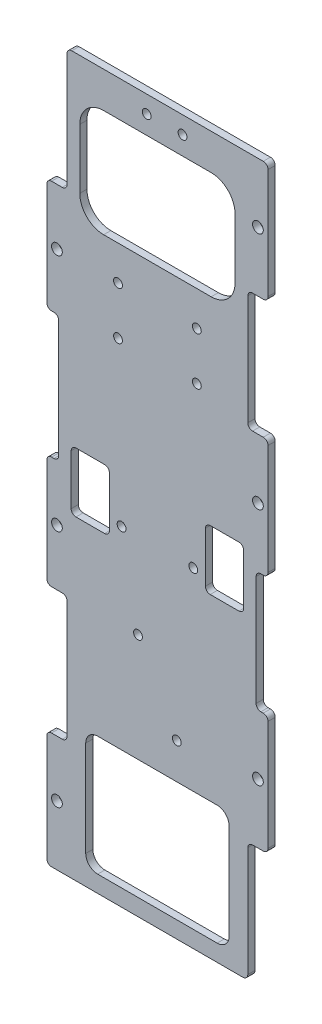
SolidWorks part; units mm, degrees
material "Acrylic (Medium-high impact)"
ref_plane "Front Plane" through (0, 0, 0) normal (0, 0, 1) x (1, 0, 0)
ref_plane "Top Plane" through (0, 0, 0) normal (0, 1, 0) x (1, 0, 0)
ref_plane "Right Plane" through (0, 0, 0) normal (1, 0, 0) x (0, 0, -1)
sketch "Sketch1" plane through (0, 0, 0) normal (0, 0, 1) x (1, 0, 0)
  line L1 (46.3, -150) -> (-46.3, -150)
  line L2 (46.3, -150) -> (46.3, 150)
  line L3 (46.3, 150) -> (-46.3, 150)
  line L4 (-46.3, -150) -> (-46.3, 150)
  line L5 (46.3, -150) -> (-46.3, 150) construction
  line L6 (46.3, 150) -> (-46.3, -150) construction
  point P0 (0, 0)
  dimension "D1" = 300
  dimension "D2" = 92.6
extrude "Boss-Extrude1" add sketch "Sketch1" along normal blind 3
sketch "Sketch3" plane through (0, 0, 0) normal (0, 0, 1) x (1, 0, 0)
  line L0 (-42.06, 151.5) -> (-42.06, -150) construction
  line L1 (42.06, 150) -> (42.06, -148.5) construction
  line L2 (-37.82, 98.5) -> (-46.3, 98.5)
  line L3 (-37.82, 98.5) -> (-37.82, 150)
  line L4 (-37.82, 150) -> (-46.3, 150)
  line L5 (-46.3, 98.5) -> (-46.3, 150)
  line L6 (-37.82, 98.5) -> (-46.3, 150) construction
  line L7 (-37.82, 150) -> (-46.3, 98.5) construction
  line L8 (37.82, 100) -> (46.3, 100)
  line L9 (37.82, 100) -> (37.82, 50)
  line L10 (37.82, 50) -> (46.3, 50)
  line L11 (46.3, 100) -> (46.3, 50)
  line L12 (37.82, 100) -> (46.3, 50) construction
  line L13 (37.82, 50) -> (46.3, 100) construction
  line L14 (46.3, -50) -> (41.3, -50)
  line L15 (46.3, -50) -> (46.3, 0)
  line L16 (46.3, 0) -> (41.3, 0)
  line L17 (41.3, -50) -> (41.3, 0)
  line L18 (46.3, -50) -> (41.3, 0) construction
  line L19 (46.3, 0) -> (41.3, -50) construction
  line L20 (-41.3, -1.5) -> (-46.3, -1.5)
  line L21 (-41.3, -1.5) -> (-41.3, 51.5)
  line L22 (-41.3, 51.5) -> (-46.3, 51.5)
  line L23 (-46.3, -1.5) -> (-46.3, 51.5)
  line L24 (-41.3, -1.5) -> (-46.3, 51.5) construction
  line L25 (-41.3, 51.5) -> (-46.3, -1.5) construction
  line L26 (-37.82, -101.5) -> (-46.3, -101.5)
  line L27 (-37.82, -101.5) -> (-37.82, -48.5)
  line L28 (-37.82, -48.5) -> (-46.3, -48.5)
  line L29 (-46.3, -101.5) -> (-46.3, -48.5)
  line L30 (-37.82, -101.5) -> (-46.3, -48.5) construction
  line L31 (-37.82, -48.5) -> (-46.3, -101.5) construction
  line L32 (37.82, -150) -> (46.3, -150)
  line L33 (37.82, -150) -> (37.82, -100)
  line L34 (37.82, -100) -> (46.3, -100)
  line L35 (46.3, -150) -> (46.3, -100)
  line L36 (37.82, -150) -> (46.3, -100) construction
  line L37 (37.82, -100) -> (46.3, -150) construction
  line L38 (42.06, 50) -> (-134.3061, 50) construction
  line L39 (46.3, 150) -> (-46.3, 150) construction
  line L40 (-46.3, -150) -> (46.3, -150) construction
  line L41 (46.3, -150) -> (46.3, 150) construction
  line L42 (-46.3, 150) -> (-46.3, -150) construction
  circle A0 centre (-42.06, 75) radius 2.25
  circle A1 centre (42.06, 125) radius 2.25
  circle A2 centre (42.06, 25) radius 2.25
  circle A3 centre (42.06, -75) radius 2.25
  circle A4 centre (-42.06, -25) radius 2.25
  circle A5 centre (-42.06, -125) radius 2.25
  point P8 (-42.06, 124.25)
  point P10 (-42.06, 25)
  point P19 (42.06, 75)
  point P24 (-42.06, -75)
  point P32 (43.8, -25)
  point P39 (42.06, -125)
  dimension "D1" = 4.5
  dimension "D2" = 4.5
  dimension "D12" = 4.5
  dimension "D14" = 4.5
  dimension "D20" = 4.5
  dimension "D22" = 4.5
  dimension "D3" = 25
  dimension "D4" = 84.12
  dimension "D5" = 8.48
  dimension "D6" = 51.5
  dimension "D7" = 8.48
  dimension "D8" = 50
  dimension "D9" = 50
  dimension "D10" = 5
  dimension "D11" = 75
  dimension "D13" = 125
  dimension "D15" = 100
  dimension "D16" = 53
  dimension "D17" = 53
  dimension "D18" = 8.48
  dimension "D19" = 75
  dimension "D21" = 50
  dimension "D23" = 5
  dimension "D24" = 100
  dimension "D25" = 42.06
  dimension "D26" = 0
  dimension "D27" = 0
  dimension "D28" = 0
  dimension "D29" = 0
  dimension "D30" = 175
  dimension "D31" = 25
  dimension "D32" = 125
  dimension "D33" = 75
  dimension "D34" = 0
  dimension "D35" = 0
extrude "Cut-Extrude2" cut sketch "Sketch3" along normal blind 10
fillet "Fillet1" radius 2 24 edges at (-41.3, -1.5, 1.5) (-46.3, -1.5, 1.5) (-46.3, -48.5, 1.5) (-37.82, -48.5, 1.5) (-37.82, -101.5, 1.5) (-46.3, -101.5, 1.5) (-46.3, -150, 1.5) (37.82, -150, 1.5) (37.82, -100, 1.5) (46.3, -100, 1.5) (46.3, -50, 1.5) (41.3, -50, 1.5) (41.3, 0, 1.5) (46.3, 0, 1.5) (46.3, 50, 1.5) (37.82, 50, 1.5) (37.82, 100, 1.5) (46.3, 100, 1.5) (46.3, 150, 1.5) (-37.82, 150, 1.5) (-37.82, 98.5, 1.5) (-46.3, 98.5, 1.5) (-41.3, 51.5, 1.5) (-46.3, 51.5, 1.5)
sketch "Sketch4" plane through (0, 0, 0) normal (0, 0, -1) x (-1, 0, 0)
  circle A2 centre (8.125, -47.8) radius 1.85
  circle A3 centre (-8.125, -78) radius 1.85
  dimension "D1" = 3.7
  dimension "D2" = 3.7
extrude "Cut-Extrude3" cut sketch "Sketch4" against normal blind 5
sketch "Sketch5" plane through (0, 0, 0) normal (0, 0, -1) x (-1, 0, 0)
  line L10 (-34.8, -5.6) -> (34.8, -5.6) construction
  line L15 (-34.8, 3.65) -> (-34.8, -14.85) construction
  line L17 (34.8, -14.85) -> (34.8, 3.65) construction
  line L18 (-28.1, 3.65) -> (-28.1, -17) construction
  line L19 (-21.4, 3.65) -> (-34.8, 3.65) construction
  line L20 (-33.6, -17) -> (-22.6, -17) construction
  line L21 (28.1, 3.65) -> (28.1, -17) construction
  line L22 (34.8, 3.65) -> (21.4, 3.65) construction
  line L23 (22.6, -17) -> (33.6, -17) construction
  line L25 (-22.1, -18.1) -> (-34.1, -18.1)
  line L26 (-20.1, -16.1) -> (-20.1, 4.9)
  line L27 (-22.1, 6.9) -> (-34.1, 6.9)
  line L28 (-36.1, -16.1) -> (-36.1, 4.9)
  line L29 (-20.1, -18.1) -> (-36.1, 6.9) construction
  line L30 (-20.1, 6.9) -> (-36.1, -18.1) construction
  line L31 (34.1, -18.1) -> (22.1, -18.1)
  line L32 (36.1, -16.1) -> (36.1, 4.9)
  line L33 (34.1, 6.9) -> (22.1, 6.9)
  line L34 (20.1, -16.1) -> (20.1, 4.9)
  line L35 (36.1, -18.1) -> (20.1, 6.9) construction
  line L36 (36.1, 6.9) -> (20.1, -18.1) construction
  circle A15 centre (-15, -12) radius 1.85
  circle A16 centre (15, -12) radius 1.85
  arc A17 (22.1, -18.1) -> (20.1, -16.1) centre (22.1, -16.1) cw
  arc A18 (34.1, -18.1) -> (36.1, -16.1) centre (34.1, -16.1) ccw
  arc A19 (36.1, 4.9) -> (34.1, 6.9) centre (34.1, 4.9) ccw
  arc A20 (22.1, 6.9) -> (20.1, 4.9) centre (22.1, 4.9) ccw
  arc A21 (-34.1, -18.1) -> (-36.1, -16.1) centre (-34.1, -16.1) cw
  arc A22 (-20.1, 4.9) -> (-22.1, 6.9) centre (-22.1, 4.9) ccw
  arc A23 (-22.1, -18.1) -> (-20.1, -16.1) centre (-22.1, -16.1) ccw
  arc A24 (-34.1, 6.9) -> (-36.1, 4.9) centre (-34.1, 4.9) ccw
  point P20 (-28.1, -5.6)
  point P25 (28.1, -5.6)
  dimension "D1" = 16
  dimension "D2" = 25
  dimension "D3" = 25
  dimension "D5" = 3.7
  dimension "D6" = 3.7
  dimension "D7" = 2
  dimension "D4" = 16
extrude "Cut-Extrude4" cut sketch "Sketch5" against normal blind 10
sketch "Sketch6" plane through (0, 0, 0) normal (0, 0, -1) x (-1, 0, 0)
  circle A4 centre (16.5, 55.5) radius 1.85
  circle A5 centre (-16.5, 55.5) radius 1.85
  circle A6 centre (-16.5, 75.5) radius 1.85
  circle A7 centre (16.5, 75.5) radius 1.85
  dimension "D1" = 3.7
extrude "Cut-Extrude5" cut sketch "Sketch6" against normal blind 8.5
sketch "Sketch7" plane through (0, 0, 0) normal (0, 0, -1) x (-1, 0, 0)
  line L0 (0, 148) -> (0, -150) construction
  line L11 (-44.3, 150) -> (35.82, 150) construction
  line L12 (22.5, 90) -> (-22.5, 90)
  line L13 (-42, -148) -> (42, -148) construction
  line L14 (25, -143) -> (-25, -143)
  line L15 (30, -138) -> (30, -98)
  line L16 (25, -93) -> (-25, -93)
  line L17 (-30, -138) -> (-30, -98)
  line L18 (30, -143) -> (-30, -93) construction
  line L19 (30, -93) -> (-30, -143) construction
  line L21 (32.5, 100) -> (32.5, 125)
  line L22 (22.5, 135) -> (-22.5, 135)
  line L23 (-32.5, 100) -> (-32.5, 125)
  line L24 (32.5, 90) -> (-32.5, 135) construction
  line L25 (32.5, 135) -> (-32.5, 90) construction
  arc A4 (-25, -93) -> (-30, -98) centre (-25, -98) ccw
  arc A5 (-25, -143) -> (-30, -138) centre (-25, -138) cw
  arc A6 (25, -143) -> (30, -138) centre (25, -138) ccw
  arc A7 (30, -98) -> (25, -93) centre (25, -98) ccw
  arc A8 (22.5, 90) -> (32.5, 100) centre (22.5, 100) ccw
  arc A9 (-22.5, 90) -> (-32.5, 100) centre (-22.5, 100) cw
  arc A10 (-22.5, 135) -> (-32.5, 125) centre (-22.5, 125) ccw
  arc A11 (32.5, 125) -> (22.5, 135) centre (22.5, 125) ccw
  point P4 (0, 112.5)
  point P12 (0, -118)
  dimension "D7" = 15
  dimension "D3" = 10
  dimension "D1" = 65
  dimension "D2" = 45
  dimension "D4" = 50
  dimension "D5" = 60
  dimension "D6" = 5
extrude "Cut-Extrude6" cut sketch "Sketch7" against normal blind 8.5
sketch "Sketch9" plane through (0, 0, 0) normal (0, 0, -1) x (-1, 0, 0)
  line L0 (-3, 145) -> (-3, 140.5) construction
  line L1 (15.7, 145) -> (-21.7, 145) construction
  line L2 (15.7, 140.5) -> (-21.7, 140.5) construction
  line L3 (16.1805, 142.75) -> (-22.1805, 142.75) construction
  circle A0 centre (-10.5, 142.75) radius 1.85
  circle A1 centre (4.5, 142.75) radius 1.85
  point P9 (-3, 142.75)
  dimension "D1" = 3.7
  dimension "D2" = 3.7
  dimension "D3" = 15
  dimension "D4" = 7.5
extrude "Cut-Extrude7" cut sketch "Sketch9" against normal blind 10
